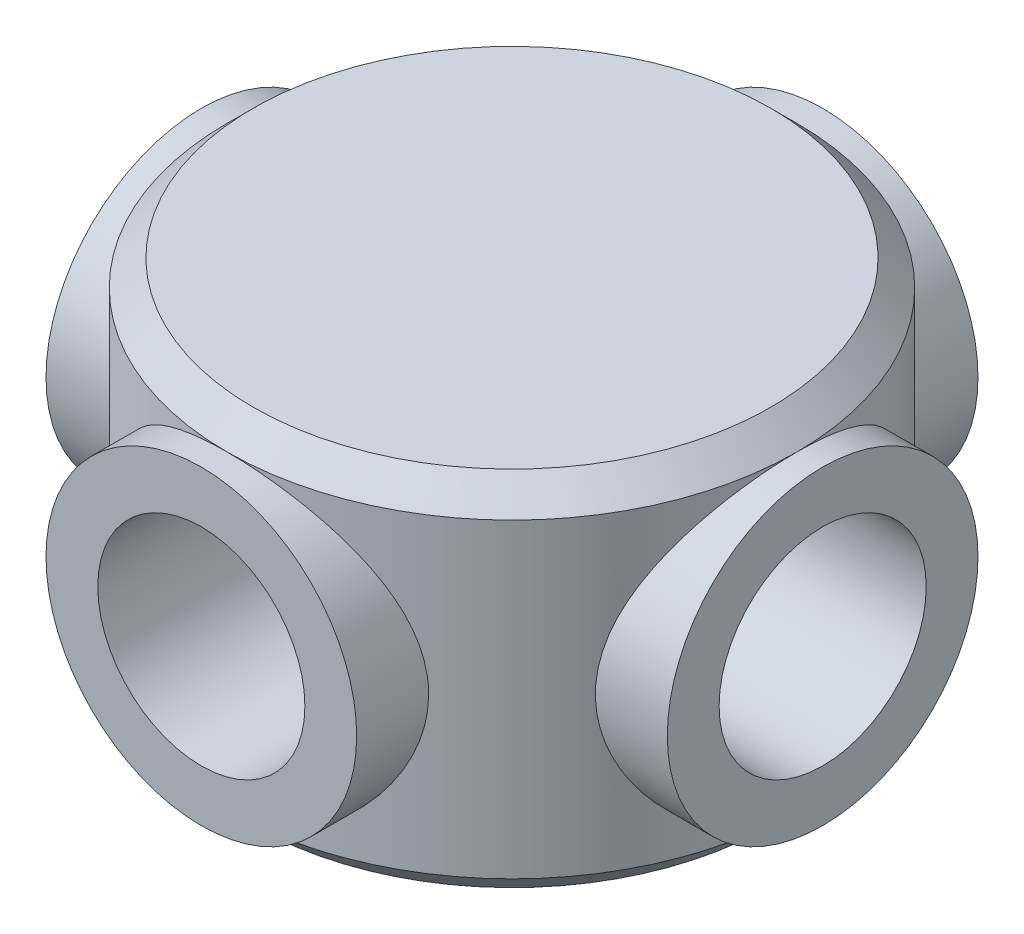
SolidWorks part; units mm, degrees
ref_plane "Alzado" through (0, 0, 0) normal (0, 0, 1) x (1, 0, 0)
ref_plane "Planta" through (0, 0, 0) normal (0, 1, 0) x (1, 0, 0)
ref_plane "Vista lateral" through (0, 0, 0) normal (1, 0, 0) x (0, 0, -1)
sketch "Croquis1" plane through (0, 0, 0) normal (1, 0, 0) x (0, 0, -1)
  line L0 (0, 0) -> (0, 14) construction
  line L1 (0, 14) -> (11, 14)
  line L2 (11, 14) -> (11, 0)
  line L3 (11, 0) -> (0, 0)
  line L4 (0, 0) -> (0, 14)
  dimension "D1" = 22
  dimension "D2" = 14
revolve "Revolución1" add sketch "Croquis1" angle 360 about L0
chamfer "Chaflán1" distance 1 angle 45 2 edges at (0, 0, -11) (0, 14, -11)
ref_plane "Plano1" through (0, 0, 12) normal (0, 0, 1) x (1, 0, 0)
sketch "Croquis2" plane through (0, 0, 12) normal (0, 0, 1) x (1, 0, 0)
  line L0 (11, 7) -> (0, 7) construction
  line L1 (11, 1) -> (11, 13) construction
  line L2 (0, 7) -> (0, 0) construction
  circle A0 centre (0, 7) radius 6
  dimension "D1" = 12
extrude "Saliente-Extruir1" add sketch "Croquis2" against normal up to surface (2.7805 mm away)
pattern_circular "MatrizC1" count 4 over 360 about axis through (0, 0, 0) along (0, 1, 0) of "Saliente-Extruir1"
sketch "Croquis4" plane through (0, 0, 0) normal (0, 0, 1) x (1, 0, 0)
  line L0 (3.5, 7) -> (12, 7)
  line L1 (12, 1) -> (12, 13) construction
  line L3 (3.5, 7) -> (5, 3)
  line L4 (5, 3) -> (12, 3)
  line L5 (12, 3) -> (12, 7)
  line L6 (3.5, 7) -> (12, 7) construction
  point P0 (0, 0)
  point P7 (2.2852, 7)
  point P10 (0, 0)
  dimension "D1" = 7
  dimension "D2" = 2
  dimension "D4" = 8.5
revolve "Cortar-Revolución1" cut sketch "Croquis4" angle 360 about L6
pattern_circular "MatrizC4" count 4 over 360 about axis through (0, 14, 0) along (0, 1, 0) of "Cortar-Revolución1"
